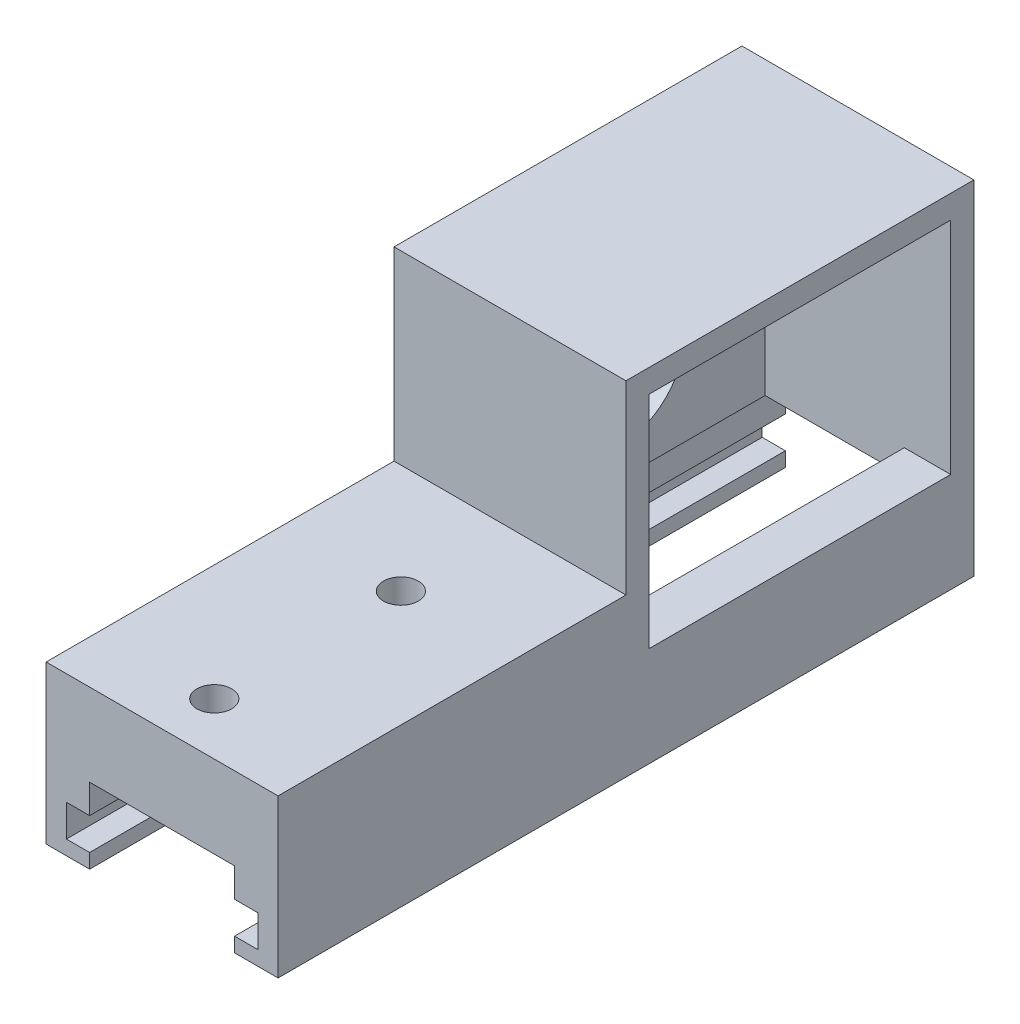
SolidWorks part; units mm, degrees
ref_plane "Front Plane" through (0, 0, 0) normal (0, 0, 1) x (1, 0, 0)
ref_plane "Top Plane" through (0, 0, 0) normal (0, 1, 0) x (1, 0, 0)
ref_plane "Right Plane" through (0, 0, 0) normal (1, 0, 0) x (0, 0, -1)
sketch "Sketch1" plane through (0, 0, 0) normal (0, 0, 1) x (1, 0, 0)
  line L1 (-9.0828, 5.2367) -> (10.9172, 5.2367)
  line L2 (-9.0828, 5.2367) -> (-9.0828, -8.3633)
  line L3 (-9.0828, -8.3633) -> (10.9172, -8.3633)
  line L4 (10.9172, 5.2367) -> (10.9172, -8.3633)
  dimension "D1" = 20
  dimension "D2" = 13.6
extrude "Boss-Extrude1" add sketch "Sketch1" against normal blind 65
sketch "Sketch2" plane through (0, 0, 0) normal (0, 0, 1) x (1, 0, 0)
  line L0 (-5.3328, -8.3633) -> (-5.3328, -7.1133)
  line L1 (-9.0828, -8.3633) -> (10.9172, -8.3633) construction
  line L2 (-5.3328, -7.1133) -> (-7.3328, -7.1133)
  line L3 (-7.3328, -7.1133) -> (-7.3328, -4.3633)
  line L4 (-7.3328, -4.3633) -> (-5.3328, -4.3633)
  line L5 (-5.3328, -4.3633) -> (-5.3328, -1.8633)
  line L6 (0.9172, -8.3633) -> (0.9172, 1.6367) construction
  line L7 (-9.0828, 5.2367) -> (-9.0828, -8.3633) construction
  line L8 (-5.3328, -1.8633) -> (7.1672, -1.8633)
  line L9 (-5.3328, -8.3633) -> (7.1672, -8.3633)
  line L10 (7.1672, -8.3633) -> (7.1672, -7.1133)
  line L11 (7.1672, -7.1133) -> (9.1672, -7.1133)
  line L12 (9.1672, -7.1133) -> (9.1672, -4.3633)
  line L13 (9.1672, -4.3633) -> (7.1672, -4.3633)
  line L14 (7.1672, -4.3633) -> (7.1672, -1.8633)
  point P19 (0.9172, -1.8633)
  dimension "D1" = 3.75
  dimension "D2" = 1.25
  dimension "D3" = 2
  dimension "D4" = 2.75
  dimension "D5" = 2
  dimension "D6" = 2.5
sketch "Sketch3" plane through (0, 5.2367, 0) normal (0, 1, 0) x (1, 0, 0)
  line L0 (10.9172, 0) -> (-9.0828, 0) construction
  line L1 (-9.0828, 65) -> (-9.0828, 0) construction
  circle A0 centre (0.9172, 4.5) radius 1.5
  circle A1 centre (0.9172, 20.5894) radius 1.5
  dimension "D1" = 3
  dimension "D3" = 10
  dimension "D2" = 4.5
extrude "Cut-Extrude2" cut sketch "Sketch3" against normal through all
sketch "Sketch5" plane through (10.9172, 0, 0) normal (1, 0, 0) x (0, 0, -1)
  line L1 (65, 5.2367) -> (30, 5.2367)
  line L2 (65, 5.2367) -> (65, 0.2367)
  line L3 (65, 0.2367) -> (30, 0.2367)
  line L4 (30, 5.2367) -> (30, 0.2367)
  dimension "D1" = 5
  dimension "D2" = 35
extrude "Cut-Extrude4" cut sketch "Sketch5" against normal through all
sketch "Sketch6" plane through (0, 0.2367, 0) normal (0, 1, 0) x (1, 0, 0)
  line L0 (-9.0828, 30) -> (-9.0828, 65) construction
  line L1 (-5.0828, 63) -> (6.9172, 63)
  line L2 (-5.0828, 63) -> (-5.0828, 32)
  line L3 (-5.0828, 32) -> (6.9172, 32)
  line L4 (6.9172, 63) -> (6.9172, 32)
  line L5 (10.9172, 30) -> (10.9172, 65) construction
  line L6 (-9.0828, 65) -> (10.9172, 65) construction
  line L7 (-9.0828, 30) -> (10.9172, 30) construction
  dimension "D1" = 4
  dimension "D2" = 4
  dimension "D3" = 2
  dimension "D4" = 2
extrude "Cut-Extrude5" cut sketch "Sketch6" against normal blind 5
sketch "Sketch7" plane through (0, 0.2367, 0) normal (0, 1, 0) x (1, 0, 0)
  line L0 (10.9172, 30) -> (10.9172, 65) construction
  line L1 (-9.0828, 30) -> (10.9172, 30) construction
  line L2 (-9.0828, 30) -> (-9.0828, 65) construction
  line L3 (-9.0828, 65) -> (10.9172, 65) construction
  line L4 (10.9172, 30) -> (10.9172, 65)
  line L5 (-9.0828, 30) -> (10.9172, 30)
  line L6 (-9.0828, 30) -> (-9.0828, 65)
  line L7 (-9.0828, 65) -> (10.9172, 65)
extrude "Boss-Extrude2" add sketch "Sketch7" along normal blind 21
sketch "Sketch8" plane through (10.9172, 0, 0) normal (1, 0, 0) x (0, 0, -1)
  line L0 (30, 21.2367) -> (65, 21.2367) construction
  line L1 (32, 19.2367) -> (63, 19.2367)
  line L2 (32, 19.2367) -> (32, 0.2367)
  line L3 (32, 0.2367) -> (63, 0.2367)
  line L4 (63, 19.2367) -> (63, 0.2367)
  line L5 (65, -8.3633) -> (65, 21.2367) construction
  line L6 (30, 21.2367) -> (30, 5.2367) construction
  line L7 (30, 5.2367) -> (0, 5.2367) construction
  point P8 (65, 6.4367)
  dimension "D1" = 2
  dimension "D2" = 2
  dimension "D3" = 2
  dimension "D4" = 5
extrude "Cut-Extrude6" cut sketch "Sketch8" against normal blind 16
sketch "Sketch9" plane through (-5.0828, 0, 0) normal (1, 0, 0) x (0, 0, -1)
  line L0 (63, 19.2367) -> (32, 19.2367) construction
  line L1 (63, -4.7633) -> (63, 19.2367) construction
  line L2 (37.3857, 8.5858) -> (43.1, 11.2963)
  line L3 (37.3857, 3.8876) -> (43.1, 1.177)
  arc A0 (43.1, 1.177) -> (43.1, 11.2963) centre (45.5, 6.2367) ccw
  arc A1 (37.3857, 8.5858) -> (37.3857, 3.8876) centre (38.5, 6.2367) ccw
  circle A2 centre (45.5, 6.2367) radius 11 construction
  dimension "D1" = 11.2
  dimension "D2" = 5.2
  dimension "D3" = 13
  dimension "D4" = 17.5
  dimension "D5" = 7
  dimension "D6" = 22
extrude "Cut-Extrude7" cut sketch "Sketch9" against normal through all
sketch "Sketch11" plane through (10.9172, 0, 0) normal (1, 0, 0) x (0, 0, -1)
  line L0 (65, -8.3633) -> (0, -8.3633) construction
  line L1 (65, 21.2367) -> (60, 21.2367)
  line L2 (65, 21.2367) -> (65, -8.3633)
  line L3 (65, -8.3633) -> (60, -8.3633)
  line L4 (60, 21.2367) -> (60, -8.3633)
  dimension "D1" = 5
extrude "Cut-Extrude8" cut sketch "Sketch11" against normal through all
sketch "Sketch12" plane through (10.9172, 0, 0) normal (1, 0, 0) x (0, 0, -1)
  line L0 (60, -8.3633) -> (0, -8.3633) construction
  line L1 (60, 21.2367) -> (58, 21.2367)
  line L2 (60, 21.2367) -> (60, -8.3633)
  line L3 (60, -8.3633) -> (58, -8.3633)
  line L4 (58, 21.2367) -> (58, -8.3633)
  dimension "D1" = 2
extrude "Boss-Extrude3" add sketch "Sketch12" against normal up to surface (20 mm away) up to face at (-9.0828, 6.0367, -30)
extrude "Cut-Extrude9" cut sketch "Sketch2" against normal through all
sketch "Sketch13" plane through (0, -1.8633, 0) normal (0, -1, 0) x (1, 0, 0)
  line L0 (7.1672, 0) -> (-5.3328, 0) construction
  line L1 (2.5072, -7.254) -> (4.0972, -4.5)
  line L2 (4.0972, -4.5) -> (2.5072, -1.746)
  line L3 (2.5072, -1.746) -> (-0.6728, -1.746)
  line L4 (-0.6728, -1.746) -> (-2.2628, -4.5)
  line L5 (-2.2628, -4.5) -> (-0.6728, -7.254)
  line L6 (-0.6728, -7.254) -> (2.5072, -7.254)
  line L7 (2.5072, -23.3434) -> (4.0972, -20.5894)
  line L8 (4.0972, -20.5894) -> (2.5072, -17.8354)
  line L9 (2.5072, -17.8354) -> (-0.6728, -17.8354)
  line L10 (-0.6728, -17.8354) -> (-2.2628, -20.5894)
  line L11 (-2.2628, -20.5894) -> (-0.6728, -23.3434)
  line L12 (-0.6728, -23.3434) -> (2.5072, -23.3434)
  circle A0 centre (0.9172, -4.5) radius 2.754 construction
  circle A1 centre (0.9172, -20.5894) radius 2.754 construction
  dimension "D1" = 3.18
extrude "Cut-Extrude10" cut sketch "Sketch13" against normal blind 4
